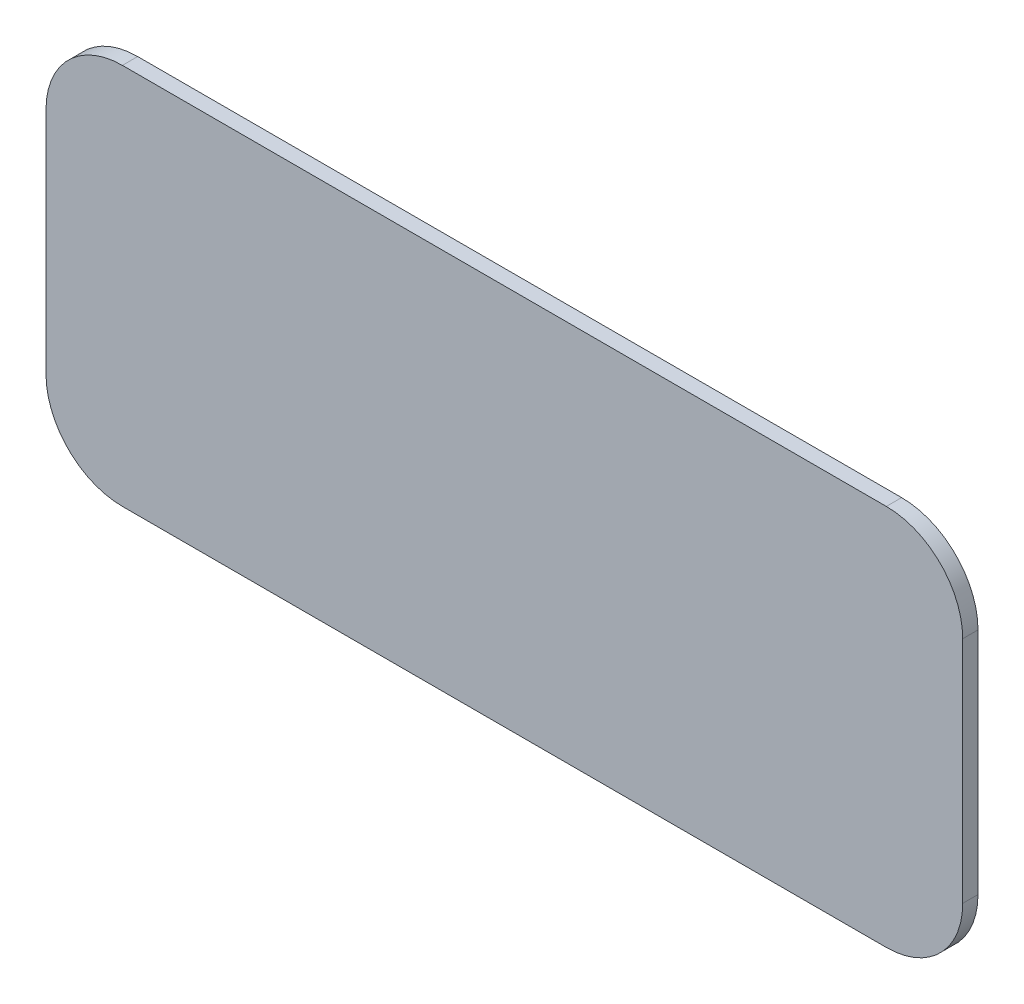
SolidWorks part; units mm, degrees
ref_plane "Front Plane" through (0, 0, 0) normal (0, 0, 1) x (1, 0, 0)
ref_plane "Top Plane" through (0, 0, 0) normal (0, 1, 0) x (1, 0, 0)
ref_plane "Right Plane" through (0, 0, 0) normal (1, 0, 0) x (0, 0, -1)
sketch "Sketch1" plane through (0, 0, 0) normal (0, 0, 1) x (1, 0, 0)
  line L8 (50, 28.0073) -> (-50, 28.0073)
  line L9 (-60, 18.0073) -> (-60, -11.9927)
  line L10 (-50, -21.9927) -> (50, -21.9927)
  line L11 (60, -11.9927) -> (60, 18.0073)
  arc A8 (60, 18.0073) -> (50, 28.0073) centre (50, 18.0073) ccw
  arc A9 (-50, 28.0073) -> (-60, 18.0073) centre (-50, 18.0073) ccw
  arc A10 (-60, -11.9927) -> (-50, -21.9927) centre (-50, -11.9927) ccw
  arc A11 (50, -21.9927) -> (60, -11.9927) centre (50, -11.9927) ccw
extrude "Boss-Extrude1" add sketch "Sketch1" along normal blind 2
